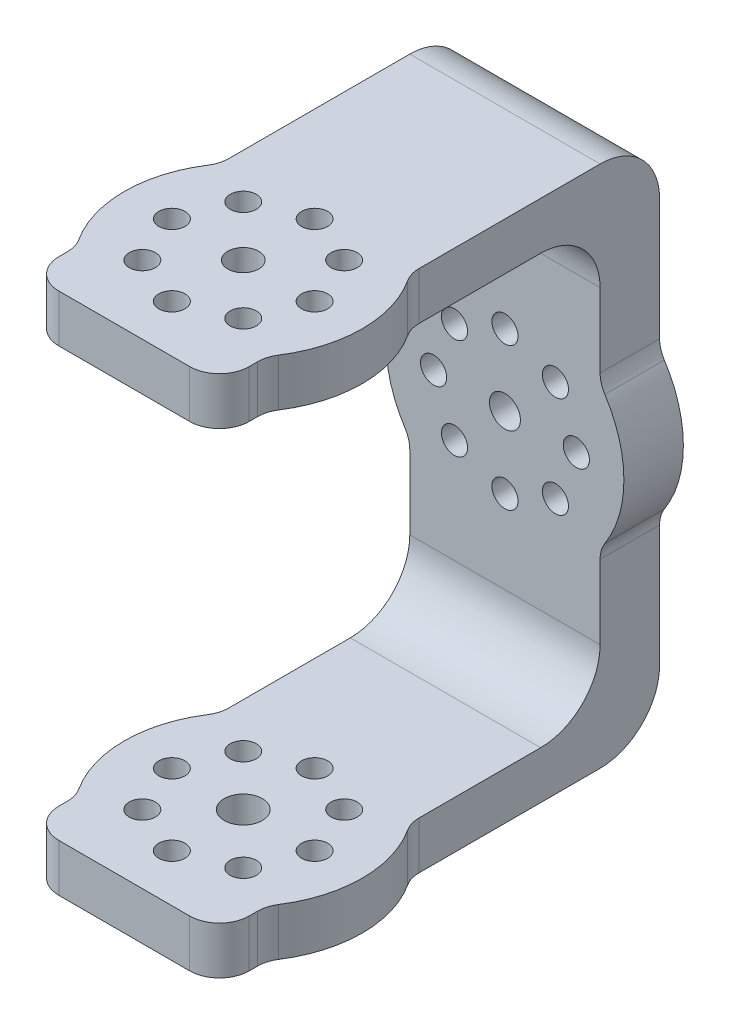
SolidWorks part; units mm, degrees
material "ABS"
ref_plane "正面" through (0, 0, 0) normal (0, 0, 1) x (1, 0, 0)
ref_plane "平面" through (0, 0, 0) normal (0, 1, 0) x (1, 0, 0)
ref_plane "右側面" through (0, 0, 0) normal (1, 0, 0) x (0, 0, -1)
sketch "ｽｹｯﾁ1" plane through (0, 0, 0) normal (0, 0, 1) x (1, 0, 0)
  line L0 (0, 0) -> (0, 36) construction
  line L1 (-8, 0) -> (8, 0)
  line L2 (-8, 0) -> (-8, 12)
  line L3 (-8, 36) -> (8, 36)
  line L4 (8, 0) -> (8, 12)
  line L5 (-8, 24) -> (-8, 36)
  line L6 (8, 24) -> (8, 36)
  circle A0 centre (0, 18) radius 6 construction
  circle A1 centre (0, 18) radius 1.3
  circle A2 centre (0, 24) radius 1.1
  circle A3 centre (4.2426, 22.2426) radius 1.1
  circle A4 centre (6, 18) radius 1.1
  circle A5 centre (4.2426, 13.7574) radius 1.1
  circle A6 centre (0, 12) radius 1.1
  circle A7 centre (-4.2426, 13.7574) radius 1.1
  circle A8 centre (-6, 18) radius 1.1
  circle A9 centre (-4.2426, 22.2426) radius 1.1
  arc A10 (-8, 24) -> (-8, 12) centre (0, 18) ccw
  arc A11 (8, 12) -> (8, 24) centre (0, 18) ccw
  point P29 (0, 18)
  dimension "D3" = 2.6
  dimension "D4" = 12
  dimension "D5" = 2.2
  dimension "D7" = 20
  dimension "D1" = 16
  dimension "D2" = 36
  dimension "D6" = 8
extrude "ﾎﾞｽ - 押し出し1" add sketch "ｽｹｯﾁ1" along normal blind 5
sketch "ｽｹｯﾁ2" plane through (0, 0, 0) normal (0, -1, 0) x (1, 0, 0)
  line L0 (8, 5) -> (8, 0) construction
  line L1 (-8, 0) -> (8, 0)
  line L2 (-8, 0) -> (-8, 21)
  line L3 (-8, 37) -> (8, 37)
  line L4 (8, 0) -> (8, 21)
  line L5 (0, 37) -> (0, 0) construction
  line L6 (-8, 33) -> (-8, 37)
  line L7 (8, 33) -> (8, 37)
  circle A0 centre (0, 27) radius 1.6
  circle A1 centre (0, 27) radius 6 construction
  circle A2 centre (6, 27) radius 1.1
  circle A3 centre (4.2426, 22.7574) radius 1.1
  circle A4 centre (0, 21) radius 1.1
  circle A5 centre (-4.2426, 22.7574) radius 1.1
  circle A6 centre (-6, 27) radius 1.1
  circle A7 centre (-4.2426, 31.2426) radius 1.1
  circle A8 centre (0, 33) radius 1.1
  circle A9 centre (4.2426, 31.2426) radius 1.1
  arc A10 (-8, 33) -> (-8, 21) centre (0, 27) ccw
  arc A11 (8, 21) -> (8, 33) centre (0, 27) ccw
  point P32 (0, 27)
  dimension "D2" = 12
  dimension "D3" = 3.2
  dimension "D5" = 2.2
  dimension "D7" = 10
  dimension "D1" = 37
  dimension "D4" = 10
  dimension "D6" = 8
extrude "ﾎﾞｽ - 押し出し2" add sketch "ｽｹｯﾁ2" along normal blind 4
sketch "ｽｹｯﾁ3" plane through (0, 36, 0) normal (0, 1, 0) x (1, 0, 0)
  line L0 (8, -5) -> (8, 0)
  line L1 (8, 0) -> (-8, 0)
  line L2 (-8, 0) -> (-8, -5)
  line L6 (8, -5) -> (-8, -5)
  line L7 (-8, -5) -> (-8, -21)
  line L8 (-8, -33) -> (-8, -37)
  line L9 (-8, -37) -> (8, -37)
  line L10 (8, -37) -> (8, -33)
  line L11 (8, -21) -> (8, -5)
  line L13 (-8, -5) -> (-8, -21)
  line L14 (-8, -33) -> (-8, -37)
  line L15 (-8, -37) -> (8, -37)
  line L16 (8, -37) -> (8, -33)
  line L17 (8, -21) -> (8, -5)
  circle A0 centre (4.2426, -22.7574) radius 1.1 construction
  circle A1 centre (0, -21) radius 1.1 construction
  arc A2 (-8, -21) -> (-8, -33) centre (0, -27) ccw
  arc A3 (8, -33) -> (8, -21) centre (0, -27) ccw
  arc A4 (-8, -21) -> (-8, -33) centre (0, -27) ccw
  arc A5 (8, -33) -> (8, -21) centre (0, -27) ccw
  circle A6 centre (-4.2426, -22.7574) radius 1.1 construction
  circle A7 centre (-6, -27) radius 1.1 construction
  circle A8 centre (-4.2426, -31.2426) radius 1.1 construction
  circle A9 centre (0, -33) radius 1.1 construction
  circle A10 centre (4.2426, -31.2426) radius 1.1 construction
  circle A11 centre (6, -27) radius 1.1 construction
  circle A12 centre (4.2426, -22.7574) radius 1.1
  circle A13 centre (0, -21) radius 1.1
  circle A14 centre (-4.2426, -22.7574) radius 1.1
  circle A15 centre (-6, -27) radius 1.1
  circle A16 centre (-4.2426, -31.2426) radius 1.1
  circle A17 centre (0, -33) radius 1.1
  circle A18 centre (4.2426, -31.2426) radius 1.1
  circle A19 centre (6, -27) radius 1.1
  circle A20 centre (0, -27) radius 1.3
  dimension "D2" = 2.6
  dimension "D1" = 0
extrude "ﾎﾞｽ - 押し出し3" add sketch "ｽｹｯﾁ3" along normal blind 4
fillet "ﾌｨﾚｯﾄ1" radius 5 4 edges at (0, 40, 0) (0, -4, 0) (0, 0, 5) (0, 36, 5)
fillet "ﾌｨﾚｯﾄ2" radius 2.5 16 edges at (8, 24, 2.5) (8, 12, 2.5) (8, 38, 21) (8, 38, 33) (8, 38, 37) (-8, 38, 37) (-8, 38, 33) (-8, 38, 21) (-8, 24, 2.5) (-8, 12, 2.5) (-8, -2, 21) (-8, -2, 33) (-8, -2, 37) (8, -2, 37) (8, -2, 21) (8, -2, 33)
